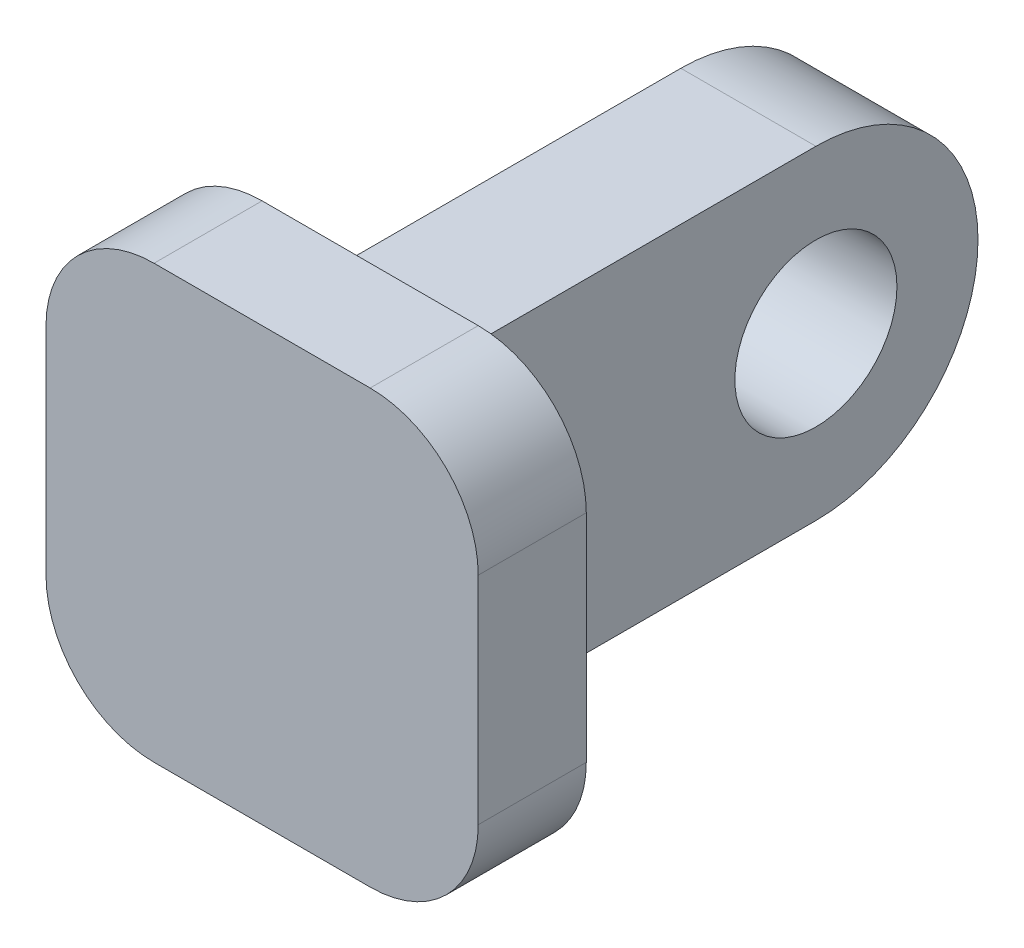
SolidWorks part; units mm, degrees
ref_plane "Plano frontal" through (0, 0, 0) normal (0, 0, 1) x (1, 0, 0)
ref_plane "Plano superior" through (0, 0, 0) normal (0, 1, 0) x (1, 0, 0)
ref_plane "Plano direito" through (0, 0, 0) normal (1, 0, 0) x (0, 0, -1)
sketch "Sketch1" plane through (0, 0, 0) normal (0, 0, 1) x (1, 0, 0)
  line L1 (-4, 4) -> (4, 4)
  line L2 (-4, 4) -> (-4, -4)
  line L3 (-4, -4) -> (4, -4)
  line L4 (4, 4) -> (4, -4)
  point P4 (0, 4)
  point P6 (-4, 0)
  dimension "D1" = 8
  dimension "D2" = 8
extrude "Boss-Extrude1" add sketch "Sketch1" along normal mid plane 2
fillet "Fillet1" radius 2 4 edges at (4, -4, 0) (-4, -4, 0) (-4, 4, 0) (4, 4, 0)
sketch "Sketch2" plane through (0, 0, 0) normal (1, 0, 0) x (0, 0, -1)
  line L0 (1, -2) -> (1, 2) construction
  line L1 (1, 3) -> (8, 3)
  line L2 (1, 3) -> (1, -3)
  line L3 (1, -3) -> (8, -3)
  arc A0 (8, -3) -> (8, 3) centre (8, 0) ccw
  point P6 (1, 0)
  point P8 (9.4235, 1.1885)
  dimension "D2" = 10
  dimension "D1" = 6
extrude "Boss-Extrude2" add sketch "Sketch2" along normal mid plane 2.5
sketch "Sketch3" plane through (0, 0, 0) normal (1, 0, 0) x (0, 0, -1)
  line L1 (8, 3) -> (1, 3) construction
  circle A0 centre (8, 0) radius 1.5
  arc A1 (8, -3) -> (8, 3) centre (8, 0) ccw construction
  point P2 (0, 0)
  dimension "D1" = 3
  dimension "D2" = 1.5
extrude "Cut-Extrude1" cut sketch "Sketch3" against normal through all both and the other way through all
